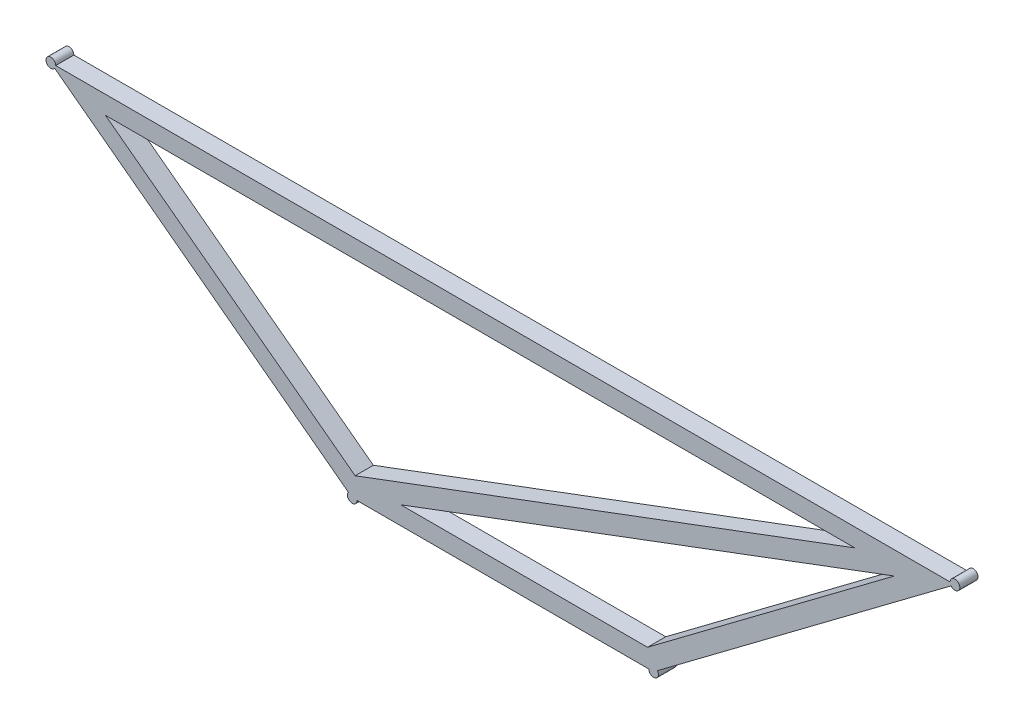
SolidWorks part; units mm, degrees
material "Plain Carbon Steel"
ref_plane "Front Plane" through (0, 0, 0) normal (0, 0, 1) x (1, 0, 0)
ref_plane "Top Plane" through (0, 0, 0) normal (0, 1, 0) x (1, 0, 0)
ref_plane "Right Plane" through (0, 0, 0) normal (1, 0, 0) x (0, 0, -1)
sketch "Sketch3" plane through (0, 0, 0) normal (0, 0, 1) x (1, 0, 0)
  line L0 (6.42, 0) -> (393.58, 0)
  line L1 (405.136, 3.852) -> (794.864, 296.148)
  line L2 (793.58, 300) -> (-393.58, 300)
  line L3 (-394.864, 296.148) -> (-5.136, 3.852)
  line L4 (64.3733, 24.14) -> (719.5333, 269.825)
  line L6 (-327.58, 275.86) -> (3.9053, 27.246)
  line L7 (3.9053, 27.246) -> (666.8759, 275.86)
  line L8 (64.3733, 24.14) -> (391.9533, 24.14)
  line L9 (391.9533, 24.14) -> (719.5333, 269.825)
  line L10 (666.8759, 275.86) -> (-327.58, 275.86)
  line L11 (-8.4761, 22.603) -> (791.5239, 322.603) construction
  line L12 (800, 300) -> (-400, 300) construction
  line L13 (391.9533, 24.14) -> (785.516, 319.312) construction
  line L14 (0, 0) -> (800, 300) construction
  line L15 (-400, 300) -> (0, 0) construction
  line L16 (800, 275.86) -> (-327.58, 275.86) construction
  line L17 (0, 24.14) -> (391.9533, 24.14) construction
  line L18 (-327.58, 275.86) -> (14.484, 19.312) construction
  line L19 (400, 0) -> (800, 300) construction
  line L20 (0, 0) -> (400, 0) construction
  arc A0 (-393.58, 300) -> (-394.864, 296.148) centre (-400, 300) ccw
  arc A1 (794.864, 296.148) -> (793.58, 300) centre (800, 300) ccw
  arc A2 (393.58, 0) -> (405.136, 3.852) centre (400, 0) ccw
  arc A3 (-5.136, 3.852) -> (6.42, 0) centre (0, 0) ccw
  point P3 (0, 0)
  point P19 (0, 0)
  point P27 (0, 0)
  dimension "D5" = 12.84
  dimension "D9" = 12.84
  dimension "D10" = 12.84
  dimension "D11" = 12.84
  dimension "D1" = 400
  dimension "D2" = 400
  dimension "D3" = 300
  dimension "D4" = 400
  dimension "D6" = 24.14
  dimension "D7" = 24.14
  dimension "D8" = 24.14
extrude "Boss-Extrude1" add sketch "Sketch3" along normal blind 24.14
